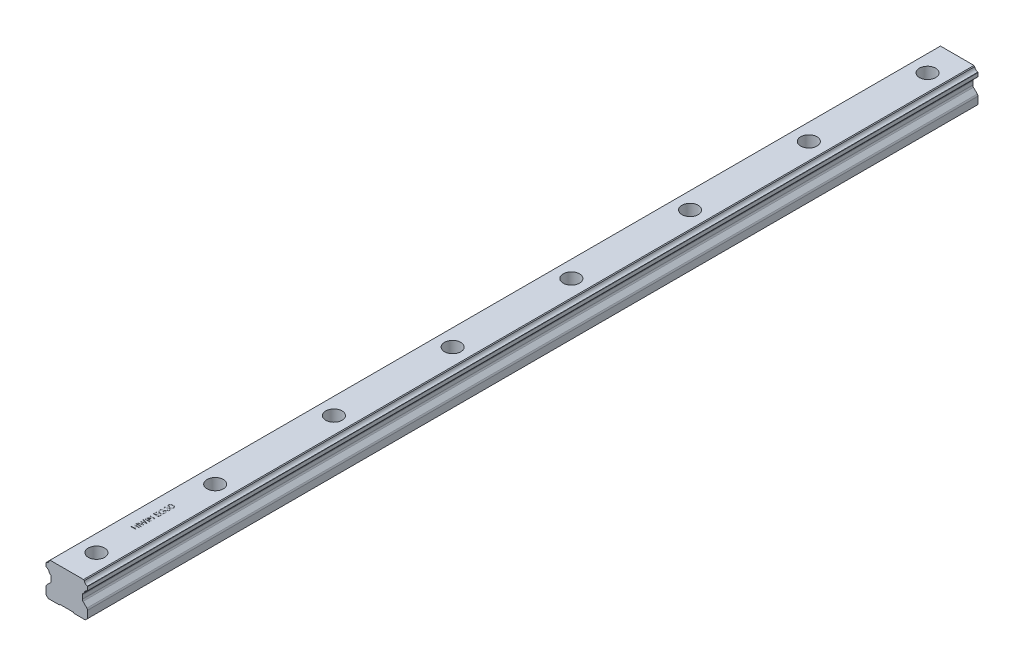
SolidWorks part; units mm, degrees
material "镀铬不锈钢"
ref_plane "前视基准面" through (0, 0, 0) normal (0, 0, 1) x (1, 0, 0)
ref_plane "上视基准面" through (0, 0, 0) normal (0, 1, 0) x (1, 0, 0)
ref_plane "右视基准面" through (0, 0, 0) normal (1, 0, 0) x (0, 0, -1)
sketch "草图1" plane through (0, 0, 0) normal (0, 0, 1) x (1, 0, 0)
  line L22 (-5, 0) -> (5, 0) construction
  line L23 (-5, 0) -> (-4.5, 0.5)
  line L24 (-4.5, 0.5) -> (4.5, 0.5)
  line L25 (5, 0) -> (12.5, 0)
  line L26 (-14, 6.3787) -> (-14, 1.5)
  line L27 (-10.9393, 10.0607) -> (-13.5607, 7.4393)
  line L28 (0, 0) -> (0, 23) construction
  line L29 (-12.5, 0) -> (-5, 0)
  line L30 (-14, 1.5) -> (-12.5, 0)
  line L31 (12.5, 0) -> (14, 1.5)
  line L32 (-10.5, 13.5787) -> (-10.5, 11.1213)
  line L33 (10.9393, 14.6393) -> (11.7582, 15.4582)
  line L34 (11.7582, 22.5418) -> (11.3, 23)
  line L35 (14, 1.5) -> (14, 6.3787)
  line L36 (-14, 20.152) -> (-14, 17.848)
  line L37 (11.3, 23) -> (-11.3, 23)
  line L38 (13.5607, 7.4393) -> (10.9393, 10.0607)
  line L39 (14, 17.848) -> (14, 20.152)
  line L40 (4.5, 0.5) -> (5, 0)
  line L41 (10.5, 11.1213) -> (10.5, 13.5787)
  line L42 (-11.7582, 15.4582) -> (-10.9393, 14.6393)
  line L43 (-11.3, 23) -> (-11.7582, 22.5418)
  arc A18 (-10.9393, 10.0607) -> (-10.5, 11.1213) centre (-12, 11.1213) ccw
  arc A19 (11.7782, 22.5198) -> (11.7582, 22.5418) centre (11.5461, 22.3297) ccw
  arc A20 (11.7582, 15.4582) -> (11.7782, 15.4802) centre (11.5461, 15.6703) ccw
  arc A21 (13.8926, 17.618) -> (11.7782, 15.4802) centre (14.2555, 15.1445) ccw
  arc A22 (-11.7582, 22.5418) -> (-11.7782, 22.5198) centre (-11.5461, 22.3297) ccw
  arc A23 (-14, 17.848) -> (-13.8926, 17.618) centre (-13.7, 17.848) ccw
  arc A24 (13.8926, 17.618) -> (14, 17.848) centre (13.7, 17.848) ccw
  arc A25 (14, 20.152) -> (13.8926, 20.382) centre (13.7, 20.152) ccw
  arc A26 (10.9393, 14.6393) -> (10.5, 13.5787) centre (12, 13.5787) ccw
  arc A27 (-13.8926, 20.382) -> (-14, 20.152) centre (-13.7, 20.152) ccw
  arc A28 (-13.8926, 20.382) -> (-11.7782, 22.5198) centre (-14.2555, 22.8555) ccw
  arc A29 (11.7782, 22.5198) -> (13.8926, 20.382) centre (14.2555, 22.8555) ccw
  arc A30 (-11.7782, 15.4802) -> (-13.8926, 17.618) centre (-14.2555, 15.1445) ccw
  arc A31 (14, 6.3787) -> (13.5607, 7.4393) centre (12.5, 6.3787) ccw
  arc A32 (-11.7782, 15.4802) -> (-11.7582, 15.4582) centre (-11.5461, 15.6703) ccw
  arc A33 (-10.5, 13.5787) -> (-10.9393, 14.6393) centre (-12, 13.5787) ccw
  arc A34 (-13.5607, 7.4393) -> (-14, 6.3787) centre (-12.5, 6.3787) ccw
  arc A35 (10.5, 11.1213) -> (10.9393, 10.0607) centre (12, 11.1213) ccw
extrude "凸台-拉伸1" add sketch "草图1" against normal blind 600
hole_wizard "M6 六角凹头螺钉的柱形沉头孔1" positions "草图3" profile "草图2" counterbore size "M6" standard "ISO" end condition through all
sketch "草图3" plane through (-2.1871, 23, -4.0788) normal (0, 1, 0) x (-1, 0, 0)
  point P0 (-2.1871, -15.9212)
  dimension "D1" = 20
sketch "草图2" plane through (0, 23, -20) normal (1, 0, 0) x (0, 0, 1)
  line L0 (0, 0) -> (0, 23)
  line L1 (0, 23) -> (3.5, 23)
  line L3 (3.5, 23) -> (3.5, 9)
  line L4 (3.5, 9) -> (5.5, 9)
  line L5 (5.5, 9) -> (5.5, 0)
  line L7 (5.5, 0) -> (0, 0)
  line L11 (0, -6.35) -> (0, 107.95) construction
  dimension "通孔孔直径" = 7
  dimension "通孔孔深度" = 23
  dimension "柱形沉头孔直径" = 11
  dimension "柱形沉头孔深度" = 9
pattern_linear "阵列(线性)1" count 8 spacing 80 along (0, 0, -1) of "M6 六角凹头螺钉的柱形沉头孔1"
sketch "草图6" plane through (0, 23, 0) normal (0, 1, 0) x (1, 0, 0)
  line L0 (0, 20) -> (0, 100) construction
  text T0 "HIWIN EG30"
extrude "切除-拉伸1" cut sketch "草图6" against normal blind 0.1
equation "\"D1@凸台-拉伸1\" = 2 * \"D1@草图3\" + \"D3@阵列(线性)1\" *  ( \"D1@阵列(线性)1\"  - 1) "
